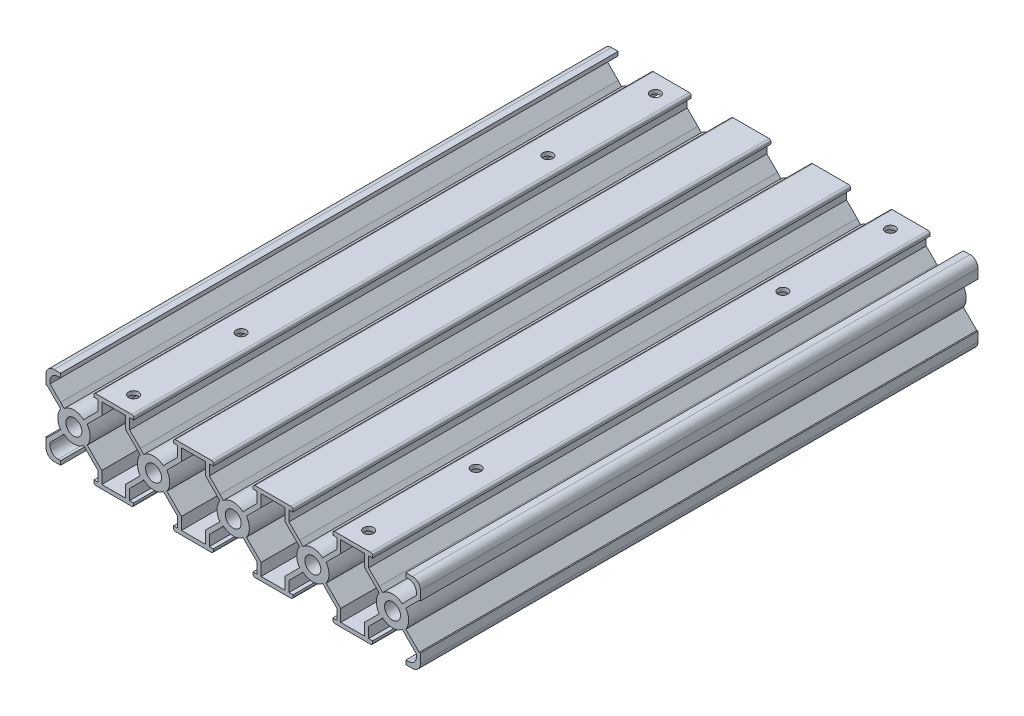
SolidWorks part; units mm, degrees
ref_plane "Front Plane" through (0, 0, 0) normal (0, 0, 1) x (1, 0, 0)
ref_plane "Top Plane" through (0, 0, 0) normal (0, 1, 0) x (1, 0, 0)
ref_plane "Right Plane" through (0, 0, 0) normal (1, 0, 0) x (0, 0, -1)
sketch "Sketch1" plane through (0, 0, 0) normal (0, 0, 1) x (1, 0, 0)
  line L0 (36.6564, 3.7071) -> (34, 6.3635)
  line L1 (-36.6564, 3.7071) -> (-43.3436, 3.7071)
  line L2 (-43.3436, -3.7071) -> (-36.6564, -3.7071)
  line L3 (-46.7071, -5.6564) -> (-47.0036, -5.6564)
  line L4 (-46.7071, 5.6564) -> (-47.0036, 5.6564)
  line L8 (-43.3436, -3.7071) -> (-46, -6.3635)
  line L9 (-46, -6.3635) -> (-46, -7)
  line L10 (-44, -9) -> (-43.3436, -9)
  line L13 (-43.3436, -9) -> (-43.3436, -10)
  line L14 (-43.3436, -10) -> (-45.0036, -10)
  line L15 (-47.0036, -8) -> (-47.0036, -5.6564)
  line L16 (-44.0507, -3) -> (-46.7071, -5.6564)
  line L19 (-44.0507, 3) -> (-44.0507, -3)
  line L20 (-44.0507, 3) -> (-46.7071, 5.6564)
  line L21 (-47.0036, 8) -> (-47.0036, 5.6564)
  line L22 (-43.3436, 10) -> (-45.0036, 10)
  line L25 (6, -9) -> (5, -9)
  line L26 (43.3436, -9) -> (43.3436, -10)
  line L27 (44.0507, 3) -> (44.0507, -3)
  line L28 (44.0507, -3) -> (46.7071, -5.6564)
  line L31 (-35.9493, -3) -> (-33, -5.9493)
  line L32 (-33, -5.9493) -> (-33, -9)
  line L33 (-15.9493, 3) -> (-15.9493, -3)
  line L34 (-7, 9) -> (-13, 9)
  line L35 (-15.9493, 3) -> (-13, 5.9493)
  line L36 (-13, 5.9493) -> (-13, 9)
  line L37 (-4.0507, 3) -> (-7, 5.9493)
  line L38 (-7, 5.9493) -> (-7, 9)
  line L39 (-33, -9) -> (-27, -9)
  line L40 (-4.0507, -3) -> (-4.0507, 3)
  line L41 (-4.0507, -3) -> (-7, -5.9493)
  line L42 (-7, -5.9493) -> (-7, -9)
  line L43 (-7, -9) -> (-13, -9)
  line L44 (-13, -5.9493) -> (-13, -9)
  line L45 (-15.9493, -3) -> (-13, -5.9493)
  line L46 (-27, -5.9493) -> (-27, -9)
  line L47 (-24.0507, -3) -> (-27, -5.9493)
  line L48 (-24.0507, 3) -> (-24.0507, -3)
  line L49 (-24.0507, 3) -> (-27, 5.9493)
  line L50 (-27, 5.9493) -> (-27, 9)
  line L51 (-33, 9) -> (-27, 9)
  line L52 (-33, 5.9493) -> (-33, 9)
  line L53 (-35.9493, 3) -> (-33, 5.9493)
  line L54 (-35.9493, -3) -> (-35.9493, 3)
  line L55 (33, -5.9493) -> (33, -9)
  line L56 (33, -9) -> (27, -9)
  line L57 (27, -5.9493) -> (27, -9)
  line L58 (24.0507, -3) -> (27, -5.9493)
  line L59 (35.9493, -3) -> (33, -5.9493)
  line L60 (35.9493, -3) -> (35.9493, 3)
  line L61 (35.9493, 3) -> (33, 5.9493)
  line L62 (33, 5.9493) -> (33, 9)
  line L63 (33, 9) -> (27, 9)
  line L64 (27, 5.9493) -> (27, 9)
  line L65 (24.0507, 3) -> (27, 5.9493)
  line L66 (24.0507, 3) -> (24.0507, -3)
  line L67 (4.0507, -3) -> (4.0507, 3)
  line L68 (4.0507, -3) -> (7, -5.9493)
  line L69 (7, -5.9493) -> (7, -9)
  line L70 (7, -9) -> (13, -9)
  line L71 (13, -5.9493) -> (13, -9)
  line L72 (15.9493, -3) -> (13, -5.9493)
  line L73 (15.9493, 3) -> (15.9493, -3)
  line L74 (15.9493, 3) -> (13, 5.9493)
  line L75 (13, 5.9493) -> (13, 9)
  line L76 (7, 9) -> (13, 9)
  line L77 (7, 5.9493) -> (7, 9)
  line L78 (4.0507, 3) -> (7, 5.9493)
  line L79 (43.3436, 3.7071) -> (36.6564, 3.7071)
  line L80 (34, 6.3635) -> (34, 9)
  line L81 (43.3436, 3.7071) -> (46, 6.3635)
  line L82 (36.6564, 3.7071) -> (33.7071, 6.6564) construction
  line L83 (34, 5.9493) -> (34, 9) construction
  line L84 (46, 6.3635) -> (46, 7)
  line L85 (44, 9) -> (43.3436, 9)
  line L86 (43.3436, 9) -> (43.3436, 10)
  line L87 (43.3436, 10) -> (45.0036, 10)
  line L88 (44.0507, 3) -> (46.7071, 5.6564)
  line L89 (43.3436, -3.7071) -> (46, -6.3635)
  line L90 (47.0036, 8) -> (47.0036, 5.6564)
  line L91 (47.0036, 5.6564) -> (46.7071, 5.6564)
  line L92 (34, 9) -> (35, 9)
  line L93 (23.3436, 3.7071) -> (26, 6.3635)
  line L94 (26, 6.3635) -> (26, 9)
  line L95 (26, 9) -> (25, 9)
  line L96 (25, 9) -> (25, 10)
  line L97 (25, 10) -> (35, 10)
  line L98 (35, 10) -> (35, 9)
  line L99 (43.3436, -3.7071) -> (36.6564, -3.7071)
  line L100 (43.3436, -10) -> (45.0036, -10)
  line L101 (44, -9) -> (43.3436, -9)
  line L102 (46, -6.3635) -> (46, -7)
  line L103 (47.0036, -8) -> (47.0036, -5.6564)
  line L104 (47.0036, -5.6564) -> (46.7071, -5.6564)
  line L105 (23.3436, -3.7071) -> (26, -6.3635)
  line L106 (26, -6.3635) -> (26, -9)
  line L107 (26, -9) -> (25, -9)
  line L108 (25, -9) -> (25, -10)
  line L109 (25, -10) -> (35, -10)
  line L110 (35, -10) -> (35, -9)
  line L111 (34, -9) -> (35, -9)
  line L112 (34, -6.3635) -> (34, -9)
  line L113 (36.6564, -3.7071) -> (34, -6.3635)
  line L114 (23.3436, 3.7071) -> (16.6564, 3.7071)
  line L115 (5, -10) -> (5, -9)
  line L116 (15, -10) -> (5, -10)
  line L117 (15, -9) -> (15, -10)
  line L118 (14, -9) -> (15, -9)
  line L119 (16.6564, -3.7071) -> (14, -6.3635)
  line L120 (14, -6.3635) -> (14, -9)
  line L121 (6, -6.3635) -> (6, -9)
  line L122 (3.3436, -3.7071) -> (6, -6.3635)
  line L123 (3.3436, 3.7071) -> (6, 6.3635)
  line L124 (6, 6.3635) -> (6, 9)
  line L125 (6, 9) -> (5, 9)
  line L126 (5, 10) -> (5, 9)
  line L127 (15, 10) -> (5, 10)
  line L128 (15, 9) -> (15, 10)
  line L129 (14, 9) -> (15, 9)
  line L130 (14, 6.3635) -> (14, 9)
  line L131 (16.6564, 3.7071) -> (14, 6.3635)
  line L132 (23.3436, -3.7071) -> (16.6564, -3.7071)
  line L133 (3.3436, 3.7071) -> (-3.3436, 3.7071)
  line L134 (-16.6564, -3.7071) -> (-14, -6.3635)
  line L135 (-14, -6.3635) -> (-14, -9)
  line L136 (-14, -9) -> (-15, -9)
  line L137 (-15, -9) -> (-15, -10)
  line L138 (-15, -10) -> (-5, -10)
  line L139 (-5, -10) -> (-5, -9)
  line L140 (-6, -9) -> (-5, -9)
  line L141 (-6, -6.3635) -> (-6, -9)
  line L142 (-3.3436, -3.7071) -> (-6, -6.3635)
  line L143 (-3.3436, 3.7071) -> (-6, 6.3635)
  line L144 (-6, 6.3635) -> (-6, 9)
  line L145 (-6, 9) -> (-5, 9)
  line L146 (-5, 10) -> (-5, 9)
  line L147 (-15, 10) -> (-5, 10)
  line L148 (-15, 9) -> (-15, 10)
  line L149 (-14, 9) -> (-15, 9)
  line L150 (-14, 6.3635) -> (-14, 9)
  line L151 (-16.6564, 3.7071) -> (-14, 6.3635)
  line L152 (-23.3436, 3.7071) -> (-16.6564, 3.7071)
  line L153 (-23.3436, -3.7071) -> (-16.6564, -3.7071)
  line L154 (-36.6564, -3.7071) -> (-34, -6.3635)
  line L155 (-34, -6.3635) -> (-34, -9)
  line L156 (-34, -9) -> (-35, -9)
  line L157 (-35, -10) -> (-35, -9)
  line L158 (-25, -10) -> (-35, -10)
  line L159 (-25, -9) -> (-25, -10)
  line L160 (-26, -9) -> (-25, -9)
  line L161 (-26, -6.3635) -> (-26, -9)
  line L162 (-23.3436, -3.7071) -> (-26, -6.3635)
  line L163 (-23.3436, 3.7071) -> (-26, 6.3635)
  line L164 (-26, 6.3635) -> (-26, 9)
  line L165 (-26, 9) -> (-25, 9)
  line L166 (-25, 9) -> (-25, 10)
  line L167 (-25, 10) -> (-35, 10)
  line L168 (-35, 10) -> (-35, 9)
  line L169 (-34, 9) -> (-35, 9)
  line L170 (-34, 6.3635) -> (-34, 9)
  line L171 (-36.6564, 3.7071) -> (-34, 6.3635)
  line L172 (3.3436, -3.7071) -> (-3.3436, -3.7071)
  line L173 (-43.3436, 9) -> (-43.3436, 10)
  line L174 (-44, 9) -> (-43.3436, 9)
  line L175 (-46, 6.3635) -> (-46, 7)
  line L176 (-43.3436, 3.7071) -> (-46, 6.3635)
  circle A0 centre (-40, 0) radius 2
  circle A1 centre (-20, 0) radius 2
  circle A2 centre (0, 0) radius 2
  circle A3 centre (20, 0) radius 2
  circle A4 centre (40, 0) radius 2
  arc A5 (45.0036, 10) -> (47.0036, 8) centre (45.0036, 8) cw
  arc A6 (46, 7) -> (44, 9) centre (44, 7) ccw
  arc A7 (45.0036, -10) -> (47.0036, -8) centre (45.0036, -8) ccw
  arc A8 (44, -9) -> (46, -7) centre (44, -7) ccw
  arc A9 (-44, 9) -> (-46, 7) centre (-44, 7) ccw
  arc A10 (-46, -7) -> (-44, -9) centre (-44, -7) ccw
  arc A11 (-45.0036, -10) -> (-47.0036, -8) centre (-45.0036, -8) cw
  arc A12 (-47.0036, 8) -> (-45.0036, 10) centre (-45.0036, 8) cw
  point P15 (47.0036, 10)
  point P18 (46, 9)
  point P22 (47.0036, -10)
  point P26 (46, -9)
  point P30 (-46, 9)
  point P109 (-46, -9)
  point P199 (-47.0036, -10)
  point P202 (-47.0036, 10)
  dimension "D1" = 4
  dimension "D2" = 4
  dimension "D3" = 4
  dimension "D4" = 1
  dimension "D5" = 4
  dimension "D12" = 2
  dimension "D7" = 40
  dimension "D8" = 20
  dimension "D9" = 40
  dimension "D10" = 20
  dimension "D11" = 20
  dimension "D20" = 1
  dimension "D21" = 1
  dimension "D22" = 1
extrude "Boss-Extrude1" add sketch "Sketch1" along normal blind 140
sketch "Sketch3" plane through (0, 0, 0) normal (0, 0, -1) x (-1, 0, 0)
  line L0 (-44.0507, 3) -> (-43.341, 2.2903)
  line L1 (-44.0507, -3) -> (-43.341, -2.2903)
  line L3 (-44.0507, -3) -> (-44.0507, 3)
  line L4 (-36.6564, -3.7071) -> (-37.5171, -2.7528)
  line L6 (-43.3436, 3.7071) -> (-42.4829, 2.7528)
  line L7 (-36.6564, 3.7071) -> (-37.5171, 2.7528)
  line L8 (-36.6564, 3.7071) -> (-43.3436, 3.7071)
  line L9 (-35.9493, 3) -> (-36.659, 2.2903)
  line L10 (-35.9493, -3) -> (-36.659, -2.2903)
  line L11 (-35.9493, -3) -> (-35.9493, 3)
  line L12 (-36.6564, -3.7071) -> (-43.3436, -3.7071)
  line L13 (-43.3436, -3.7071) -> (-42.4829, -2.7528)
  arc A0 (-37.5171, 2.7528) -> (-42.4829, 2.7528) centre (-40, 0) ccw
  arc A1 (-43.341, 2.2903) -> (-43.341, -2.2903) centre (-40, 0) ccw
  arc A2 (-36.659, 2.2903) -> (-36.659, -2.2903) centre (-40, 0) cw
  arc A3 (-37.5171, -2.7528) -> (-42.4829, -2.7528) centre (-40, 0) cw
extrude "Cut-Extrude1" cut sketch "Sketch3" against normal through all contours A0 L8 L6 | A0 L7 L8 | L9 A2 L11 | L11 A2 L10 | L4 A3 L12 | L12 A3 L13 | A1 L3 L1 | A1 L0 L3
pattern_linear "LPattern1" count 5 spacing 20 along (-1, 0, 0) of "Cut-Extrude1"
fillet "Fillet1" radius 0.5 16 edges at (35, -10, 70) (25, -10, 70) (15, -10, 70) (5, -10, 70) (-5, -10, 70) (-15, -10, 70) (-25, -10, 70) (-35, -10, 70) (5, 10, 70) (15, 10, 70) (25, 10, 70) (35, 10, 70) (-5, 10, 70) (-15, 10, 70) (-25, 10, 70) (-35, 10, 70)
sketch "Sketch4" plane through (0, 10, 0) normal (0, 1, 0) x (1, 0, 0)
  line L3 (-47.0036, -140) -> (-47.0036, 0) construction
  line L4 (-25.5, -140) -> (-34.5, -140) construction
  line L6 (-47.0036, -70) -> (-59.156, -70)
  circle A0 centre (-29.5036, -135.5) radius 1
  circle A1 centre (-29.5036, -108.5) radius 1
  circle A2 centre (-29.5036, -31.5) radius 1
  circle A3 centre (-29.5036, -4.5) radius 1
  circle A4 centre (29.5036, -4.5) radius 1
  circle A5 centre (29.5036, -31.5) radius 1
  circle A6 centre (29.5036, -108.5) radius 1
  circle A7 centre (29.5036, -135.5) radius 1
  dimension "D5" = 2
  dimension "D6" = 2
  dimension "D1" = 27
  dimension "D2" = 17.5
  dimension "D3" = 17.5
  dimension "D4" = 4.5
extrude "Cut-Extrude2" cut sketch "Sketch4" against normal blind 12 contours A1 | A0 | A3 | A2 | A5 | A4 | A6 | A7
hole_wizard "M3x0.5 Tapped Hole1" positions "3DSketch1" profile "Sketch6" tap size "M3x0.5" standard "ANSI Metric"
sketch3d "3DSketch1"
  line L0 (-29.5036, 9, 135.5) -> (-29.5036, 10, 135.5) construction
  line L1 (-29.5036, 9, 108.5) -> (-29.5036, 10, 108.5) construction
  line L2 (-29.5036, 9, 4.5) -> (-29.5036, 10, 4.5) construction
  line L3 (-29.5036, 9, 31.5) -> (-29.5036, 10, 31.5) construction
  line L4 (29.5036, 9, 4.5) -> (29.5036, 10, 4.5) construction
  line L5 (29.5036, 9, 31.5) -> (29.5036, 10, 31.5) construction
  line L6 (29.5036, 9, 108.5) -> (29.5036, 10, 108.5) construction
  line L7 (29.5036, 9, 135.5) -> (29.5036, 10, 135.5) construction
  point P0 (-29.5036, 10, 135.5)
  point P4 (-29.5036, 10, 108.5)
  point P8 (-29.5036, 10, 4.5)
  point P12 (-29.5036, 10, 31.5)
  point P16 (29.5036, 10, 4.5)
  point P20 (29.5036, 10, 31.5)
  point P24 (29.5036, 10, 108.5)
  point P28 (29.5036, 10, 135.5)
sketch "Sketch6" plane through (-29.5036, 10, 135.5) normal (1, 0, 0) x (0, 0, 1)
  line L0 (0, 0) -> (0, 12.2511)
  line L1 (0, 12.2511) -> (1.25, 11.5)
  line L2 (1.25, 11.5) -> (1.25, 0)
  line L5 (1.25, 0) -> (0, 0)
  line L10 (0, 12.2511) -> (-1.25, 11.5) construction
  line L11 (0, -6.35) -> (0, 107.95) construction
  dimension "Tap Drill Dia." = 2.5
  dimension "Tap Drill Depth" = 11.5
  dimension "Drill Angle" = 118
cosmetic thread "Hole Thread1" parameters "D1"=1, "D2"=3
cosmetic thread "Hole Thread2" parameters "D1"=1, "D2"=3
cosmetic thread "Hole Thread3" parameters "D1"=1, "D2"=3
cosmetic thread "Hole Thread4" parameters "D1"=1, "D2"=3
cosmetic thread "Hole Thread5" parameters "D1"=1, "D2"=3
cosmetic thread "Hole Thread6" parameters "D1"=1, "D2"=3
cosmetic thread "Hole Thread7" parameters "D1"=1, "D2"=3
cosmetic thread "Hole Thread8" parameters "D1"=1, "D2"=3
sketch "Sketch7" plane through (0, 10, 0) normal (0, 1, 0) x (1, 0, 0)
  point P0 (0, -56.5)
  point P1 (0, -83.5)
sketch "Sketch8" plane through (0, -10, 0) normal (0, -1, 0) x (1, 0, 0)
  circle A0 centre (0, 56.5) radius 1
  circle A1 centre (0, 83.5) radius 1
  dimension "D1" = 2
  dimension "D2" = 2
extrude "Cut-Extrude3" cut sketch "Sketch8" against normal through all both and the other way through all
hole_wizard "M3x0.5 Tapped Hole2" positions "3DSketch2" profile "Sketch9" tap size "M3x0.5" standard "ANSI Metric"
sketch3d "3DSketch2"
  point P0 (0, 10, 56.5)
  point P3 (0, 10, 83.5)
sketch "Sketch9" plane through (0, 10, 56.5) normal (1, 0, 0) x (0, 0, 1)
  line L0 (0, 0) -> (0, 8.2511)
  line L1 (0, 8.2511) -> (1.25, 7.5)
  line L2 (1.25, 7.5) -> (1.25, 0)
  line L5 (1.25, 0) -> (0, 0)
  line L10 (0, 8.2511) -> (-1.25, 7.5) construction
  line L11 (0, -6.35) -> (0, 107.95) construction
  dimension "Tap Drill Dia." = 2.5
  dimension "Tap Drill Depth" = 7.5
  dimension "Drill Angle" = 118
